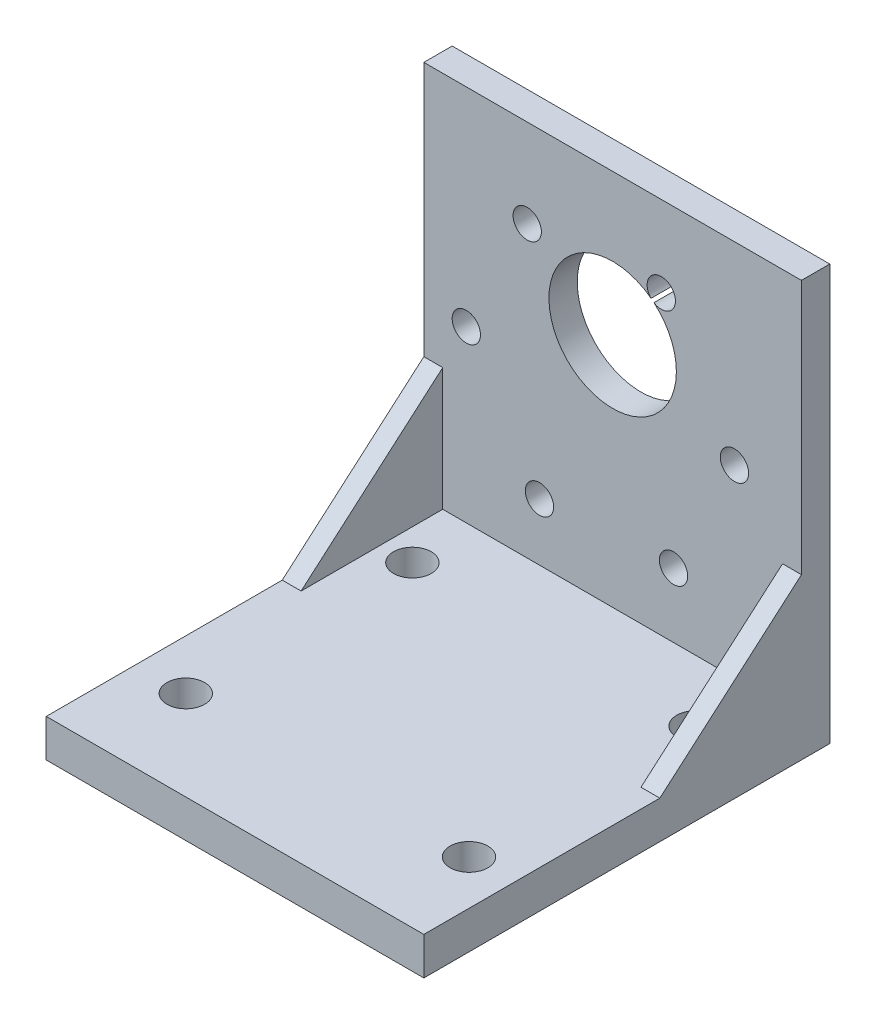
SolidWorks part; units mm, degrees
ref_plane "Front Plane" through (0, 0, 0) normal (0, 0, 1) x (1, 0, 0)
ref_plane "Top Plane" through (0, 0, 0) normal (0, 1, 0) x (1, 0, 0)
ref_plane "Right Plane" through (0, 0, 0) normal (1, 0, 0) x (0, 0, -1)
sketch "Sketch1" plane through (0, 0, 0) normal (0, 1, 0) x (1, 0, 0)
  line L0 (-20, 18.5) -> (20, 18.5)
  line L1 (-20, -21.5) -> (20, -21.5)
  line L2 (-20, -21.5) -> (-20, 21.5)
  line L3 (-20, 21.5) -> (20, 21.5)
  line L4 (20, -21.5) -> (20, 21.5)
  line L5 (-20, -21.5) -> (20, 21.5) construction
  line L6 (-20, 21.5) -> (20, -21.5) construction
  circle A7 centre (-14.7151, 12) radius 2
  circle A8 centre (15.2849, 12) radius 2
  circle A9 centre (-14.7151, -12) radius 2
  circle A10 centre (15.2849, -12) radius 2
  point P0 (0, 0)
  dimension "D4" = 30
  dimension "D5" = 4
  dimension "D6" = 4
  dimension "D7" = 24
  dimension "D8" = 9.5
  dimension "D10" = 4
  dimension "D12" = 4
  dimension "D1" = 3
  dimension "D2" = 40
  dimension "D3" = 43
extrude "Boss-Extrude1" add sketch "Sketch1" against normal blind 4
sketch "Sketch4" plane through (0, 0, 0) normal (0, 1, 0) x (1, 0, 0)
  line L1 (-20, -21.5) -> (-20, 21.5) construction
  line L2 (20, -21.5) -> (20, 21.5) construction
  line L5 (-20, 21.5) -> (20, 21.5)
  line L6 (-20, 21.5) -> (-20, 18.5)
  line L7 (-20, 18.5) -> (20, 18.5)
  line L8 (-20, -21.5) -> (20, -21.5)
  line L9 (20, -21.5) -> (20, 21.5)
  line L10 (20, 21.5) -> (-20, 21.5)
  line L11 (-20, 21.5) -> (-20, -21.5)
  line L12 (-20, -21.5) -> (20, -21.5)
  line L13 (20, -21.5) -> (20, 12.2)
  line L15 (-20, 12.2) -> (-20, -21.5)
  line L16 (20, 21.5) -> (20, 18.5)
  line M13 (20, -21.5) -> (20, 21.5)
  line M14 (20, 21.5) -> (-20, 21.5)
  line M15 (-20, 21.5) -> (-20, -21.5)
  dimension "D1" = 3
  dimension "D2" = 0
extrude "Boss-Extrude2" add sketch "Sketch4" along normal blind 40 contours L7 M15 M13 M14
sketch "Sketch5" plane through (0, 0, -18.5) normal (0, 0, 1) x (1, 0, 0)
  line L0 (-20, 40) -> (20, -4) construction
  line L1 (-20, -4) -> (20, 40) construction
  line L2 (0, 18) -> (0, 2.5) construction
  line L3 (0, 18) -> (0, 25) construction
  circle A11 centre (0, 25) radius 6.75
  point P18 (0, 18)
  point P28 (0, 18)
  dimension "D2" = 7
  dimension "D5" = 15.5
  dimension "D6" = 13.5
extrude "Cut-Extrude5" cut sketch "Sketch5" against normal blind 34
sketch "Sketch8" plane through (0, 0, -18.5) normal (0, 0, 1) x (1, 0, 0)
  line L0 (-20, 40) -> (20, -4) construction
  line L1 (20, 40) -> (-20, -4) construction
  line L2 (0, 18) -> (0, 2.5) construction
  line L3 (-20, 18) -> (20, 18) construction
  line L4 (-20, 40) -> (-20, 0) construction
  line L5 (20, 40) -> (20, 0) construction
  line L6 (15.5, 18) -> (-15.5, 18)
  circle A0 centre (0, 2.5) radius 1.5
  circle A1 centre (-15.5, 18) radius 1.5
  circle A3 centre (0, 18) radius 15.5
  circle A4 centre (-9.049, 30.6734) radius 1.5
  circle A5 centre (5.1519, 31.4234) radius 1.5
  circle A6 centre (12.9019, 19.5) radius 1.5
  circle A7 centre (6.451, 6.8266) radius 1.5
  circle A8 centre (-7.75, 6.0766) radius 1.5
  point P21 (0, 18)
  point P35 (-1.299, 18.75)
  dimension "D2" = 3
  dimension "D4" = 3
  dimension "D5" = 6
  dimension "D1" = 15.5
  dimension "D3" = 31
extrude "Cut-Extrude6" cut sketch "Sketch8" against normal blind 10 contours A7 | A6 | A5 | A4 | A1 | A8
sketch "Sketch9" plane through (20, 0, 0) normal (1, 0, 0) x (0, 0, -1)
  line L0 (18.5, 13) -> (3.5, 0)
  line L1 (18.5, 40) -> (18.5, 0) construction
  line L2 (21.5, 0) -> (-21.5, 0) construction
  line L3 (3.5, 0) -> (18.5, 0)
  line L4 (18.5, 0) -> (18.5, 13)
  dimension "D1" = 13
  dimension "D2" = 15
extrude "Boss-Extrude3" add sketch "Sketch9" against normal blind 2
sketch "Sketch10" plane through (-20, 0, 0) normal (-1, 0, 0) x (0, 0, 1)
  line L0 (-18.5, 13) -> (-3.5, 0)
  line L1 (-3.5, 0) -> (-18.5, 0)
  line L2 (-18.5, 0) -> (-18.5, 13)
extrude "Boss-Extrude4" add sketch "Sketch10" against normal blind 2
